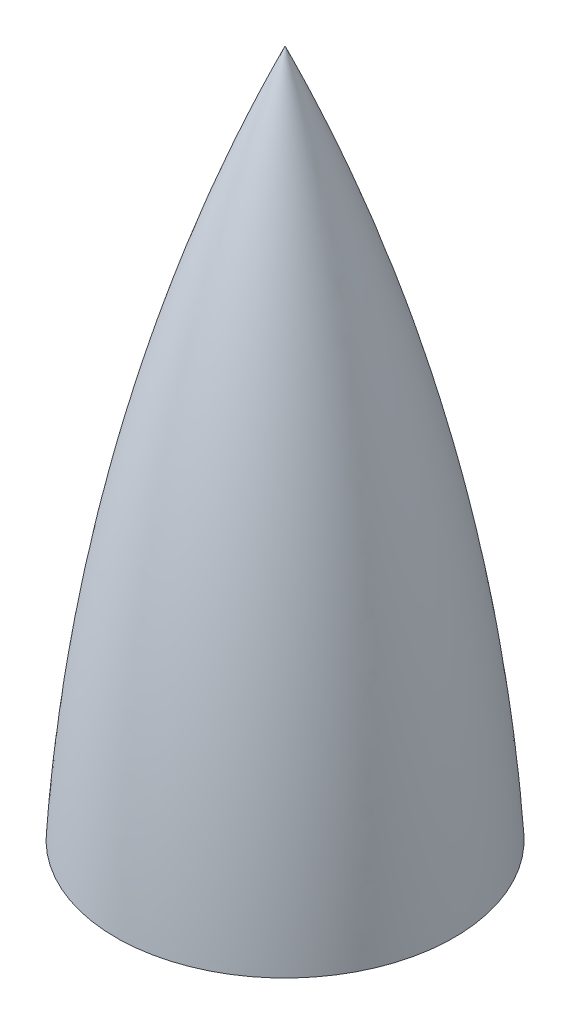
SolidWorks part; units mm, degrees
material "PVB"
ref_plane "Front Plane" through (0, 0, 0) normal (0, 0, 1) x (1, 0, 0)
ref_plane "Top Plane" through (0, 0, 0) normal (0, 1, 0) x (1, 0, 0)
ref_plane "Right Plane" through (0, 0, 0) normal (1, 0, 0) x (0, 0, -1)
sketch "Sketch2" plane through (0, 0, 0) normal (0, 0, 1) x (1, 0, 0)
  line L0 (0, 0) -> (0, 381) construction
  line L1 (-93.6498, 0) -> (-88.9, 0)
  line L2 (0, 381) -> (0, 375.92)
  arc A0 (0, 381) -> (-93.6498, 0) centre (997.7024, -66.2448) ccw
  arc A1 (0, 375.92) -> (-88.9, 0) centre (1114.6958, -86.1623) ccw
  dimension "D1" = 381
  dimension "D2" = 5.08
  dimension "D3" = 4.7498
  dimension "D4" = 88.9
revolve "Revolve1" add sketch "Sketch2" angle 360 about L2
sketch "Sketch3" plane through (0, 0, 0) normal (0, -1, 0) x (1, 0, 0)
  circle A0 centre (0, 0) radius 88.9
  circle A1 centre (0, 0) radius 86.995
  dimension "D1" = 177.8
extrude "Boss-Extrude1" [suppressed] add sketch "Sketch3" along normal blind 35.56
equation "\"D4@Sketch2\"=3.5"
